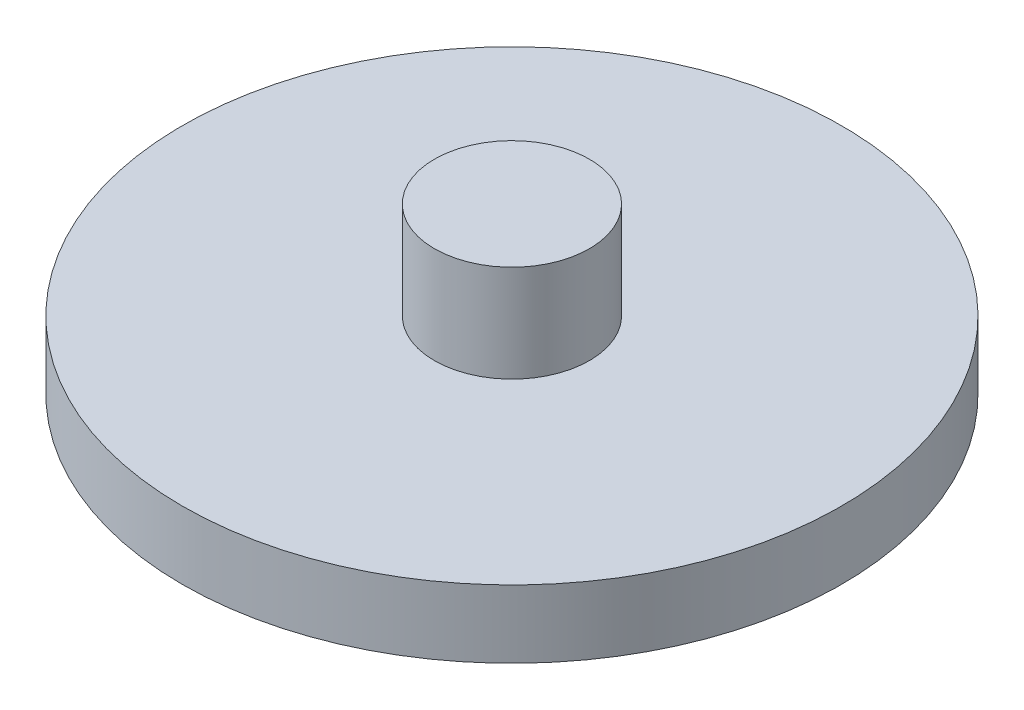
SolidWorks part; units mm, degrees
ref_plane "Front Plane" through (0, 0, 0) normal (0, 0, 1) x (1, 0, 0)
ref_plane "Top Plane" through (0, 0, 0) normal (0, 1, 0) x (1, 0, 0)
ref_plane "Right Plane" through (0, 0, 0) normal (1, 0, 0) x (0, 0, -1)
sketch "Sketch1" plane through (0, 0, 0) normal (0, 1, 0) x (1, 0, 0)
  circle A0 centre (0, 0) radius 34
  dimension "D1" = 68
extrude "Boss-Extrude1" add sketch "Sketch1" along normal blind 7
sketch "Sketch2" plane through (0, 7, 0) normal (0, 1, 0) x (1, 0, 0)
  circle A0 centre (0, 0) radius 8
  dimension "D1" = 16
extrude "Boss-Extrude2" add sketch "Sketch2" along normal blind 10
